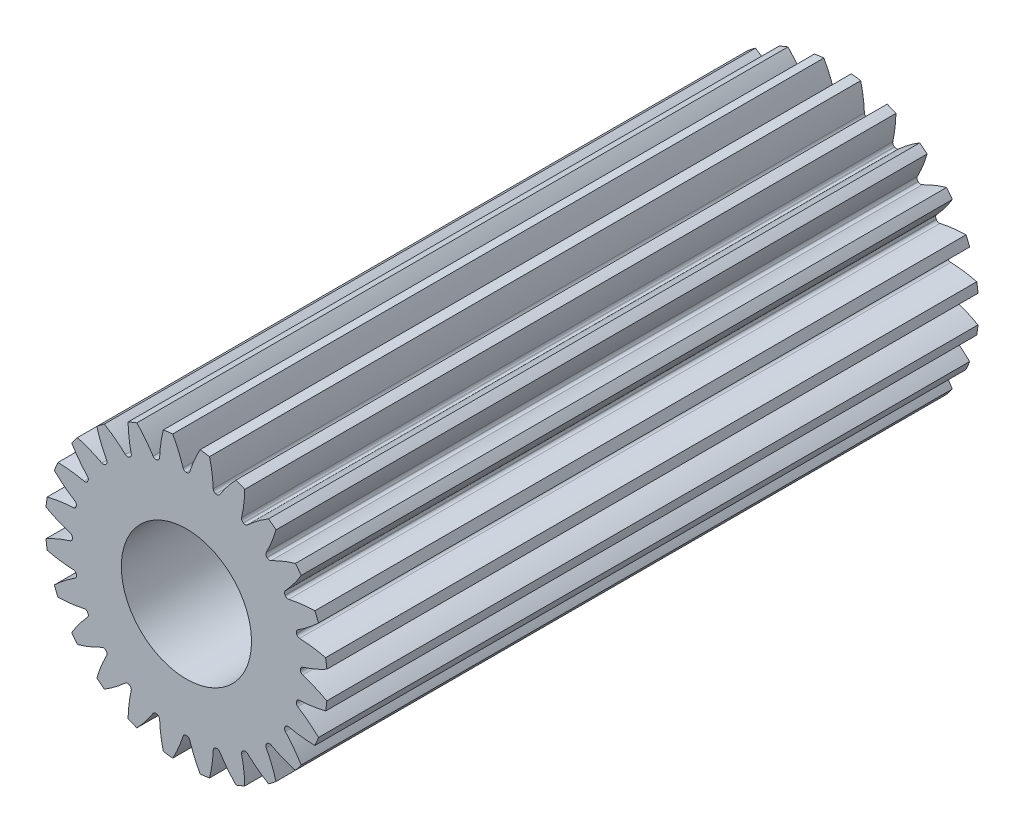
SolidWorks part; units mm, degrees
ref_plane "Front Plane" through (0, 0, 0) normal (0, 0, 1) x (1, 0, 0)
ref_plane "Top Plane" through (0, 0, 0) normal (0, 1, 0) x (1, 0, 0)
ref_plane "Right Plane" through (0, 0, 0) normal (1, 0, 0) x (0, 0, -1)
sketch "Sketch1" plane through (0, 0, 0) normal (0, 0, 1) x (1, 0, 0)
  line L0 (-304.8, 0) -> (304.8, 0) construction
  circle A0 centre (0, 0) radius 6.5 construction
  circle A1 centre (0, 0) radius 6 construction
  circle A2 centre (0, 0) radius 5.25 construction
  circle A3 centre (0, 0) radius 4 construction
  circle A4 centre (0, 0) radius 2 construction
  dimension "D2" = 0.5
  dimension "D3" = 1.25
  dimension "D1" = 1.25
sketch "Sketch2" plane through (0, 0, 0) normal (1, 0, 0) x (0, 0, -1)
  line L0 (0, 0) -> (-3, 0) construction
  line L1 (-3, 0) -> (-7, 0) construction
  dimension "Overall Width" = 7
  dimension "Face Width" = 3
sketch "Sketch4" plane through (0, 0, 0) normal (1, 0, 0) x (0, 0, -1)
  line L0 (-7, 2) -> (-7, 4) construction
  line L1 (-7, 4) -> (-3, 4) construction
  line L2 (-3, 4) -> (-3, 6.5)
  line L3 (-3, 6.5) -> (0, 6.5)
  line L4 (0, 6.5) -> (0, 2)
  line L5 (-3, 4) -> (-3, 0) construction
  line L6 (0, 6.5) -> (0, -6.5) construction
  line L7 (-3, 4) -> (0, 4) construction
  line L8 (-3, 4) -> (-3, 2)
  line L9 (-3, 2) -> (0, 2) construction
  line L10 (0, 2) -> (0, 0)
  line L11 (0, 0) -> (-3, 0)
  line L12 (-7, 2) -> (0, 2) construction
  line L13 (-3, 0) -> (-3, 2)
revolve "Revolve1" add sketch "Sketch4" angle 360 about L1
sketch "Sketch7" plane through (0, 0, 3) normal (0, 0, 1) x (1, 0, 0)
  line L0 (0, 0) -> (0, 6.5) construction
  line L1 (0.3924, 5.9872) -> (0.6056, 6.4717) construction
  line L3 (0.8484, 6.4444) -> (0.7832, 5.9487) construction
  line L4 (0.7832, 5.9487) -> (0.6853, 5.2051) construction
  line L5 (0, 0) -> (0.6853, 5.2051) construction
  line L6 (0.3924, 5.9872) -> (0, 0) construction
  line L7 (0.3924, 5.9872) -> (0.4251, 6.4861) construction
  line L8 (0.3924, 5.9872) -> (0, 0) construction
  circle A0 centre (0, 0) radius 6.5 construction
  arc A1 (-0.0123, 5.25) -> (0.0123, 5.25) centre (0, 0) cw
  circle A2 centre (0, 0) radius 5.25 construction
  arc A3 (-0.3924, 5.9872) -> (0.3924, 5.9872) centre (0, 0) cw construction
  circle A4 centre (0, 0) radius 6 construction
  arc A5 (1.065, 6.4122) -> (0.6309, 6.4693) centre (0, 0) ccw construction
  arc A6 (0.3924, 5.9872) -> (1.1705, 5.8847) centre (0, 0) cw construction
  arc A7 (-0.6309, 6.4693) -> (0.6309, 6.4693) centre (0, 0) cw
  arc A8 (0.1559, 5.3554) -> (0.6309, 6.4693) centre (5.8843, 3.5707) cw
  arc A9 (-0.1559, 5.3554) -> (-0.6309, 6.4693) centre (-5.8843, 3.5707) ccw
  arc A10 (-0.0123, 5.25) -> (-0.1559, 5.3554) centre (-0.0126, 5.4) cw
  arc A11 (0.0123, 5.25) -> (0.1559, 5.3554) centre (0.0126, 5.4) ccw
  point P26 (-0.1237, 5.2485)
  point P29 (0.1237, 5.2485)
  dimension "D4" = 0.15
  dimension "D5" = 6
  dimension "D3" = 20
  dimension "D1" = 1.5708
  dimension "D2" = 0.7854
extrude "Cut-Extrude2" cut sketch "Sketch7" against normal through all
pattern_circular "CirPattern1" count 24 over 360 about axis through (0, 0, 0) along (0, 0, 1) of "Cut-Extrude2"
sketch "Sketch8" plane through (0, 0, 3) normal (0, 0, 1) x (1, 0, 0)
  arc A144 (-1.5366, 5.1326) -> (-2.2838, 6.0856) centre (-6.6079, 1.926) ccw
  arc A145 (-2.2838, 6.0856) -> (-2.6883, 5.918) centre (0, 0) ccw
  arc A146 (-2.6883, 5.918) -> (-2.5427, 4.7158) centre (3.3106, 6.0344) ccw
  arc A147 (-2.6143, 4.5528) -> (-2.5427, 4.7158) centre (-2.689, 4.6829) ccw
  arc A148 (-2.6143, 4.5528) -> (-2.6356, 4.5405) centre (0, 0) ccw
  arc A149 (-2.8127, 4.56) -> (-2.6356, 4.5405) centre (-2.7109, 4.6702) ccw
  arc A150 (-2.8127, 4.56) -> (-3.781, 5.2871) centre (-6.8813, 0.1502) ccw
  arc A151 (-3.781, 5.2871) -> (-4.1284, 5.0206) centre (0, 0) ccw
  arc A152 (-4.1284, 5.0206) -> (-3.6766, 3.897) centre (1.636, 6.6857) ccw
  arc A153 (-3.7036, 3.721) -> (-3.6766, 3.897) centre (-3.8094, 3.8273) ccw
  arc A154 (-3.7036, 3.721) -> (-3.721, 3.7036) centre (0, 0) ccw
  arc A155 (-3.897, 3.6766) -> (-3.721, 3.7036) centre (-3.8273, 3.8094) ccw
  arc A156 (-3.897, 3.6766) -> (-5.0206, 4.1284) centre (-6.6857, -1.636) ccw
  arc A157 (-5.0206, 4.1284) -> (-5.2871, 3.781) centre (0, 0) ccw
  arc A158 (-5.2871, 3.781) -> (-4.56, 2.8127) centre (-0.1502, 6.8813) ccw
  arc A159 (-4.5405, 2.6356) -> (-4.56, 2.8127) centre (-4.6702, 2.7109) ccw
  arc A160 (-4.5405, 2.6356) -> (-4.5528, 2.6143) centre (0, 0) ccw
  arc A161 (-4.7158, 2.5427) -> (-4.5528, 2.6143) centre (-4.6829, 2.689) ccw
  arc A162 (-4.7158, 2.5427) -> (-5.918, 2.6883) centre (-6.0344, -3.3106) ccw
  arc A163 (-5.918, 2.6883) -> (-6.0856, 2.2838) centre (0, 0) ccw
  arc A164 (-6.0856, 2.2838) -> (-5.1326, 1.5366) centre (-1.926, 6.6079) ccw
  arc A165 (-5.0679, 1.3707) -> (-5.1326, 1.5366) centre (-5.2127, 1.4098) ccw
  arc A166 (-5.0679, 1.3707) -> (-5.0743, 1.3469) centre (0, 0) ccw
  arc A167 (-5.2132, 1.2355) -> (-5.0743, 1.3469) centre (-5.2193, 1.3854) ccw
  arc A168 (-5.2132, 1.2355) -> (-6.4122, 1.065) centre (-4.972, -4.7596) ccw
  arc A169 (-6.4122, 1.065) -> (-6.4693, 0.6309) centre (0, 0) ccw
  arc A170 (-6.4693, 0.6309) -> (-5.3554, 0.1559) centre (-3.5707, 5.8843) ccw
  arc A171 (-5.25, 0.0123) -> (-5.3554, 0.1559) centre (-5.4, 0.0126) ccw
  arc A172 (-5.25, 0.0123) -> (-5.25, -0.0123) centre (0, 0) ccw
  arc A173 (-5.3554, -0.1559) -> (-5.25, -0.0123) centre (-5.4, -0.0126) ccw
  arc A174 (-5.3554, -0.1559) -> (-6.4693, -0.6309) centre (-3.5707, -5.8843) ccw
  arc A175 (-6.4693, -0.6309) -> (-6.4122, -1.065) centre (0, 0) ccw
  arc A176 (-6.4122, -1.065) -> (-5.2132, -1.2355) centre (-4.972, 4.7596) ccw
  arc A177 (-5.0743, -1.3469) -> (-5.2132, -1.2355) centre (-5.2193, -1.3854) ccw
  arc A178 (-5.0743, -1.3469) -> (-5.0679, -1.3707) centre (0, 0) ccw
  arc A179 (-5.1326, -1.5366) -> (-5.0679, -1.3707) centre (-5.2127, -1.4098) ccw
  arc A180 (-5.1326, -1.5366) -> (-6.0856, -2.2838) centre (-1.926, -6.6079) ccw
  arc A181 (-6.0856, -2.2838) -> (-5.918, -2.6883) centre (0, 0) ccw
  arc A182 (-5.918, -2.6883) -> (-4.7158, -2.5427) centre (-6.0344, 3.3106) ccw
  arc A183 (-4.5528, -2.6143) -> (-4.7158, -2.5427) centre (-4.6829, -2.689) ccw
  arc A184 (-4.5528, -2.6143) -> (-4.5405, -2.6356) centre (0, 0) ccw
  arc A185 (-4.56, -2.8127) -> (-4.5405, -2.6356) centre (-4.6702, -2.7109) ccw
  arc A186 (-4.56, -2.8127) -> (-5.2871, -3.781) centre (-0.1502, -6.8813) ccw
  arc A187 (-5.2871, -3.781) -> (-5.0206, -4.1284) centre (0, 0) ccw
  arc A188 (-5.0206, -4.1284) -> (-3.897, -3.6766) centre (-6.6857, 1.636) ccw
  arc A189 (-3.721, -3.7036) -> (-3.897, -3.6766) centre (-3.8273, -3.8094) ccw
  arc A190 (-3.721, -3.7036) -> (-3.7036, -3.721) centre (0, 0) ccw
  arc A191 (-3.6766, -3.897) -> (-3.7036, -3.721) centre (-3.8094, -3.8273) ccw
  arc A192 (-3.6766, -3.897) -> (-4.1284, -5.0206) centre (1.636, -6.6857) ccw
  arc A193 (-4.1284, -5.0206) -> (-3.781, -5.2871) centre (0, 0) ccw
  arc A194 (-3.781, -5.2871) -> (-2.8127, -4.56) centre (-6.8813, -0.1502) ccw
  arc A195 (-2.6356, -4.5405) -> (-2.8127, -4.56) centre (-2.7109, -4.6702) ccw
  arc A196 (-2.6356, -4.5405) -> (-2.6143, -4.5528) centre (0, 0) ccw
  arc A197 (-2.5427, -4.7158) -> (-2.6143, -4.5528) centre (-2.689, -4.6829) ccw
  arc A198 (-2.5427, -4.7158) -> (-2.6883, -5.918) centre (3.3106, -6.0344) ccw
  arc A199 (-2.6883, -5.918) -> (-2.2838, -6.0856) centre (0, 0) ccw
  arc A200 (-2.2838, -6.0856) -> (-1.5366, -5.1326) centre (-6.6079, -1.926) ccw
  arc A201 (-1.3707, -5.0679) -> (-1.5366, -5.1326) centre (-1.4098, -5.2127) ccw
  arc A202 (-1.3707, -5.0679) -> (-1.3469, -5.0743) centre (0, 0) ccw
  arc A203 (-1.2355, -5.2132) -> (-1.3469, -5.0743) centre (-1.3854, -5.2193) ccw
  arc A204 (-1.2355, -5.2132) -> (-1.065, -6.4122) centre (4.7596, -4.972) ccw
  arc A205 (-1.065, -6.4122) -> (-0.6309, -6.4693) centre (0, 0) ccw
  arc A206 (-0.6309, -6.4693) -> (-0.1559, -5.3554) centre (-5.8843, -3.5707) ccw
  arc A207 (-0.0123, -5.25) -> (-0.1559, -5.3554) centre (-0.0126, -5.4) ccw
  arc A208 (-0.0123, -5.25) -> (0.0123, -5.25) centre (0, 0) ccw
  arc A209 (0.1559, -5.3554) -> (0.0123, -5.25) centre (0.0126, -5.4) ccw
  arc A210 (0.1559, -5.3554) -> (0.6309, -6.4693) centre (5.8843, -3.5707) ccw
  arc A211 (0.6309, -6.4693) -> (1.065, -6.4122) centre (0, 0) ccw
  arc A212 (1.065, -6.4122) -> (1.2355, -5.2132) centre (-4.7596, -4.972) ccw
  arc A213 (1.3469, -5.0743) -> (1.2355, -5.2132) centre (1.3854, -5.2193) ccw
  arc A214 (1.3469, -5.0743) -> (1.3707, -5.0679) centre (0, 0) ccw
  arc A215 (1.5366, -5.1326) -> (1.3707, -5.0679) centre (1.4098, -5.2127) ccw
  arc A216 (1.5366, -5.1326) -> (2.2838, -6.0856) centre (6.6079, -1.926) ccw
  arc A217 (2.2838, -6.0856) -> (2.6883, -5.918) centre (0, 0) ccw
  arc A218 (2.6883, -5.918) -> (2.5427, -4.7158) centre (-3.3106, -6.0344) ccw
  arc A219 (2.6143, -4.5528) -> (2.5427, -4.7158) centre (2.689, -4.6829) ccw
  arc A220 (2.6143, -4.5528) -> (2.6356, -4.5405) centre (0, 0) ccw
  arc A221 (2.8127, -4.56) -> (2.6356, -4.5405) centre (2.7109, -4.6702) ccw
  arc A222 (2.8127, -4.56) -> (3.781, -5.2871) centre (6.8813, -0.1502) ccw
  arc A223 (3.781, -5.2871) -> (4.1284, -5.0206) centre (0, 0) ccw
  arc A224 (4.1284, -5.0206) -> (3.6766, -3.897) centre (-1.636, -6.6857) ccw
  arc A225 (3.7036, -3.721) -> (3.6766, -3.897) centre (3.8094, -3.8273) ccw
  arc A226 (3.7036, -3.721) -> (3.721, -3.7036) centre (0, 0) ccw
  arc A227 (3.897, -3.6766) -> (3.721, -3.7036) centre (3.8273, -3.8094) ccw
  arc A228 (3.897, -3.6766) -> (5.0206, -4.1284) centre (6.6857, 1.636) ccw
  arc A229 (5.0206, -4.1284) -> (5.2871, -3.781) centre (0, 0) ccw
  arc A230 (5.2871, -3.781) -> (4.56, -2.8127) centre (0.1502, -6.8813) ccw
  arc A231 (4.5405, -2.6356) -> (4.56, -2.8127) centre (4.6702, -2.7109) ccw
  arc A232 (4.5405, -2.6356) -> (4.5528, -2.6143) centre (0, 0) ccw
  arc A233 (4.7158, -2.5427) -> (4.5528, -2.6143) centre (4.6829, -2.689) ccw
  arc A234 (4.7158, -2.5427) -> (5.918, -2.6883) centre (6.0344, 3.3106) ccw
  arc A235 (5.918, -2.6883) -> (6.0856, -2.2838) centre (0, 0) ccw
  arc A236 (6.0856, -2.2838) -> (5.1326, -1.5366) centre (1.926, -6.6079) ccw
  arc A237 (5.0679, -1.3707) -> (5.1326, -1.5366) centre (5.2127, -1.4098) ccw
  arc A238 (5.0679, -1.3707) -> (5.0743, -1.3469) centre (0, 0) ccw
  arc A239 (5.2132, -1.2355) -> (5.0743, -1.3469) centre (5.2193, -1.3854) ccw
  arc A240 (5.2132, -1.2355) -> (6.4122, -1.065) centre (4.972, 4.7596) ccw
  arc A241 (6.4122, -1.065) -> (6.4693, -0.6309) centre (0, 0) ccw
  arc A242 (6.4693, -0.6309) -> (5.3554, -0.1559) centre (3.5707, -5.8843) ccw
  arc A243 (5.25, -0.0123) -> (5.3554, -0.1559) centre (5.4, -0.0126) ccw
  arc A244 (5.25, -0.0123) -> (5.25, 0.0123) centre (0, 0) ccw
  arc A245 (5.3554, 0.1559) -> (5.25, 0.0123) centre (5.4, 0.0126) ccw
  arc A246 (5.3554, 0.1559) -> (6.4693, 0.6309) centre (3.5707, 5.8843) ccw
  arc A247 (6.4693, 0.6309) -> (6.4122, 1.065) centre (0, 0) ccw
  arc A248 (6.4122, 1.065) -> (5.2132, 1.2355) centre (4.972, -4.7596) ccw
  arc A249 (5.0743, 1.3469) -> (5.2132, 1.2355) centre (5.2193, 1.3854) ccw
  arc A250 (5.0743, 1.3469) -> (5.0679, 1.3707) centre (0, 0) ccw
  arc A251 (5.1326, 1.5366) -> (5.0679, 1.3707) centre (5.2127, 1.4098) ccw
  arc A252 (5.1326, 1.5366) -> (6.0856, 2.2838) centre (1.926, 6.6079) ccw
  arc A253 (6.0856, 2.2838) -> (5.918, 2.6883) centre (0, 0) ccw
  arc A254 (5.918, 2.6883) -> (4.7158, 2.5427) centre (6.0344, -3.3106) ccw
  arc A255 (4.5528, 2.6143) -> (4.7158, 2.5427) centre (4.6829, 2.689) ccw
  arc A256 (4.5528, 2.6143) -> (4.5405, 2.6356) centre (0, 0) ccw
  arc A257 (4.56, 2.8127) -> (4.5405, 2.6356) centre (4.6702, 2.7109) ccw
  arc A258 (4.56, 2.8127) -> (5.2871, 3.781) centre (0.1502, 6.8813) ccw
  arc A259 (5.2871, 3.781) -> (5.0206, 4.1284) centre (0, 0) ccw
  arc A260 (5.0206, 4.1284) -> (3.897, 3.6766) centre (6.6857, -1.636) ccw
  arc A261 (3.721, 3.7036) -> (3.897, 3.6766) centre (3.8273, 3.8094) ccw
  arc A262 (3.721, 3.7036) -> (3.7036, 3.721) centre (0, 0) ccw
  arc A263 (3.6766, 3.897) -> (3.7036, 3.721) centre (3.8094, 3.8273) ccw
  arc A264 (3.6766, 3.897) -> (4.1284, 5.0206) centre (-1.636, 6.6857) ccw
  arc A265 (4.1284, 5.0206) -> (3.781, 5.2871) centre (0, 0) ccw
  arc A266 (3.781, 5.2871) -> (2.8127, 4.56) centre (6.8813, 0.1502) ccw
  arc A267 (2.6356, 4.5405) -> (2.8127, 4.56) centre (2.7109, 4.6702) ccw
  arc A268 (2.6356, 4.5405) -> (2.6143, 4.5528) centre (0, 0) ccw
  arc A269 (2.5427, 4.7158) -> (2.6143, 4.5528) centre (2.689, 4.6829) ccw
  arc A270 (2.5427, 4.7158) -> (2.6883, 5.918) centre (-3.3106, 6.0344) ccw
  arc A271 (2.6883, 5.918) -> (2.2838, 6.0856) centre (0, 0) ccw
  arc A272 (2.2838, 6.0856) -> (1.5366, 5.1326) centre (6.6079, 1.926) ccw
  arc A273 (1.3707, 5.0679) -> (1.5366, 5.1326) centre (1.4098, 5.2127) ccw
  arc A274 (1.3707, 5.0679) -> (1.3469, 5.0743) centre (0, 0) ccw
  arc A275 (1.2355, 5.2132) -> (1.3469, 5.0743) centre (1.3854, 5.2193) ccw
  arc A276 (1.2355, 5.2132) -> (1.065, 6.4122) centre (-4.7596, 4.972) ccw
  arc A277 (1.065, 6.4122) -> (0.6309, 6.4693) centre (0, 0) ccw
  arc A278 (0.6309, 6.4693) -> (0.1559, 5.3554) centre (5.8843, 3.5707) ccw
  arc A279 (0.0123, 5.25) -> (0.1559, 5.3554) centre (0.0126, 5.4) ccw
  arc A280 (0.0123, 5.25) -> (-0.0123, 5.25) centre (0, 0) ccw
  arc A281 (-0.1559, 5.3554) -> (-0.0123, 5.25) centre (-0.0126, 5.4) ccw
  arc A282 (-0.1559, 5.3554) -> (-0.6309, 6.4693) centre (-5.8843, 3.5707) ccw
  arc A283 (-0.6309, 6.4693) -> (-1.065, 6.4122) centre (0, 0) ccw
  arc A284 (-1.065, 6.4122) -> (-1.2355, 5.2132) centre (4.7596, 4.972) ccw
  arc A285 (-1.3469, 5.0743) -> (-1.2355, 5.2132) centre (-1.3854, 5.2193) ccw
  arc A286 (-1.3469, 5.0743) -> (-1.3707, 5.0679) centre (0, 0) ccw
  arc A287 (-1.5366, 5.1326) -> (-1.3707, 5.0679) centre (-1.4098, 5.2127) ccw
  arc A288 (-1.5366, 5.1326) -> (-2.2838, 6.0856) centre (-6.6079, 1.926) ccw
  arc A289 (-2.2838, 6.0856) -> (-2.6883, 5.918) centre (0, 0) ccw
  arc A290 (-2.6883, 5.918) -> (-2.5427, 4.7158) centre (3.3106, 6.0344) ccw
  arc A291 (-2.6143, 4.5528) -> (-2.5427, 4.7158) centre (-2.689, 4.6829) ccw
  arc A292 (-2.6143, 4.5528) -> (-2.6356, 4.5405) centre (0, 0) ccw
  arc A293 (-2.8127, 4.56) -> (-2.6356, 4.5405) centre (-2.7109, 4.6702) ccw
  arc A294 (-2.8127, 4.56) -> (-3.781, 5.2871) centre (-6.8813, 0.1502) ccw
  arc A295 (-3.781, 5.2871) -> (-4.1284, 5.0206) centre (0, 0) ccw
  arc A296 (-4.1284, 5.0206) -> (-3.6766, 3.897) centre (1.636, 6.6857) ccw
  arc A297 (-3.7036, 3.721) -> (-3.6766, 3.897) centre (-3.8094, 3.8273) ccw
  arc A298 (-3.7036, 3.721) -> (-3.721, 3.7036) centre (0, 0) ccw
  arc A299 (-3.897, 3.6766) -> (-3.721, 3.7036) centre (-3.8273, 3.8094) ccw
  arc A300 (-3.897, 3.6766) -> (-5.0206, 4.1284) centre (-6.6857, -1.636) ccw
  arc A301 (-5.0206, 4.1284) -> (-5.2871, 3.781) centre (0, 0) ccw
  arc A302 (-5.2871, 3.781) -> (-4.56, 2.8127) centre (-0.1502, 6.8813) ccw
  arc A303 (-4.5405, 2.6356) -> (-4.56, 2.8127) centre (-4.6702, 2.7109) ccw
  arc A304 (-4.5405, 2.6356) -> (-4.5528, 2.6143) centre (0, 0) ccw
  arc A305 (-4.7158, 2.5427) -> (-4.5528, 2.6143) centre (-4.6829, 2.689) ccw
  arc A306 (-4.7158, 2.5427) -> (-5.918, 2.6883) centre (-6.0344, -3.3106) ccw
  arc A307 (-5.918, 2.6883) -> (-6.0856, 2.2838) centre (0, 0) ccw
  arc A308 (-6.0856, 2.2838) -> (-5.1326, 1.5366) centre (-1.926, 6.6079) ccw
  arc A309 (-5.0679, 1.3707) -> (-5.1326, 1.5366) centre (-5.2127, 1.4098) ccw
  arc A310 (-5.0679, 1.3707) -> (-5.0743, 1.3469) centre (0, 0) ccw
  arc A311 (-5.2132, 1.2355) -> (-5.0743, 1.3469) centre (-5.2193, 1.3854) ccw
  arc A312 (-5.2132, 1.2355) -> (-6.4122, 1.065) centre (-4.972, -4.7596) ccw
  arc A313 (-6.4122, 1.065) -> (-6.4693, 0.6309) centre (0, 0) ccw
  arc A314 (-6.4693, 0.6309) -> (-5.3554, 0.1559) centre (-3.5707, 5.8843) ccw
  arc A315 (-5.25, 0.0123) -> (-5.3554, 0.1559) centre (-5.4, 0.0126) ccw
  arc A316 (-5.25, 0.0123) -> (-5.25, -0.0123) centre (0, 0) ccw
  arc A317 (-5.3554, -0.1559) -> (-5.25, -0.0123) centre (-5.4, -0.0126) ccw
  arc A318 (-5.3554, -0.1559) -> (-6.4693, -0.6309) centre (-3.5707, -5.8843) ccw
  arc A319 (-6.4693, -0.6309) -> (-6.4122, -1.065) centre (0, 0) ccw
  arc A320 (-6.4122, -1.065) -> (-5.2132, -1.2355) centre (-4.972, 4.7596) ccw
  arc A321 (-5.0743, -1.3469) -> (-5.2132, -1.2355) centre (-5.2193, -1.3854) ccw
  arc A322 (-5.0743, -1.3469) -> (-5.0679, -1.3707) centre (0, 0) ccw
  arc A323 (-5.1326, -1.5366) -> (-5.0679, -1.3707) centre (-5.2127, -1.4098) ccw
  arc A324 (-5.1326, -1.5366) -> (-6.0856, -2.2838) centre (-1.926, -6.6079) ccw
  arc A325 (-6.0856, -2.2838) -> (-5.918, -2.6883) centre (0, 0) ccw
  arc A326 (-5.918, -2.6883) -> (-4.7158, -2.5427) centre (-6.0344, 3.3106) ccw
  arc A327 (-4.5528, -2.6143) -> (-4.7158, -2.5427) centre (-4.6829, -2.689) ccw
  arc A328 (-4.5528, -2.6143) -> (-4.5405, -2.6356) centre (0, 0) ccw
  arc A329 (-4.56, -2.8127) -> (-4.5405, -2.6356) centre (-4.6702, -2.7109) ccw
  arc A330 (-4.56, -2.8127) -> (-5.2871, -3.781) centre (-0.1502, -6.8813) ccw
  arc A331 (-5.2871, -3.781) -> (-5.0206, -4.1284) centre (0, 0) ccw
  arc A332 (-5.0206, -4.1284) -> (-3.897, -3.6766) centre (-6.6857, 1.636) ccw
  arc A333 (-3.721, -3.7036) -> (-3.897, -3.6766) centre (-3.8273, -3.8094) ccw
  arc A334 (-3.721, -3.7036) -> (-3.7036, -3.721) centre (0, 0) ccw
  arc A335 (-3.6766, -3.897) -> (-3.7036, -3.721) centre (-3.8094, -3.8273) ccw
  arc A336 (-3.6766, -3.897) -> (-4.1284, -5.0206) centre (1.636, -6.6857) ccw
  arc A337 (-4.1284, -5.0206) -> (-3.781, -5.2871) centre (0, 0) ccw
  arc A338 (-3.781, -5.2871) -> (-2.8127, -4.56) centre (-6.8813, -0.1502) ccw
  arc A339 (-2.6356, -4.5405) -> (-2.8127, -4.56) centre (-2.7109, -4.6702) ccw
  arc A340 (-2.6356, -4.5405) -> (-2.6143, -4.5528) centre (0, 0) ccw
  arc A341 (-2.5427, -4.7158) -> (-2.6143, -4.5528) centre (-2.689, -4.6829) ccw
  arc A342 (-2.5427, -4.7158) -> (-2.6883, -5.918) centre (3.3106, -6.0344) ccw
  arc A343 (-2.6883, -5.918) -> (-2.2838, -6.0856) centre (0, 0) ccw
  arc A344 (-2.2838, -6.0856) -> (-1.5366, -5.1326) centre (-6.6079, -1.926) ccw
  arc A345 (-1.3707, -5.0679) -> (-1.5366, -5.1326) centre (-1.4098, -5.2127) ccw
  arc A346 (-1.3707, -5.0679) -> (-1.3469, -5.0743) centre (0, 0) ccw
  arc A347 (-1.2355, -5.2132) -> (-1.3469, -5.0743) centre (-1.3854, -5.2193) ccw
  arc A348 (-1.2355, -5.2132) -> (-1.065, -6.4122) centre (4.7596, -4.972) ccw
  arc A349 (-1.065, -6.4122) -> (-0.6309, -6.4693) centre (0, 0) ccw
  arc A350 (-0.6309, -6.4693) -> (-0.1559, -5.3554) centre (-5.8843, -3.5707) ccw
  arc A351 (-0.0123, -5.25) -> (-0.1559, -5.3554) centre (-0.0126, -5.4) ccw
  arc A352 (-0.0123, -5.25) -> (0.0123, -5.25) centre (0, 0) ccw
  arc A353 (0.1559, -5.3554) -> (0.0123, -5.25) centre (0.0126, -5.4) ccw
  arc A354 (0.1559, -5.3554) -> (0.6309, -6.4693) centre (5.8843, -3.5707) ccw
  arc A355 (0.6309, -6.4693) -> (1.065, -6.4122) centre (0, 0) ccw
  arc A356 (1.065, -6.4122) -> (1.2355, -5.2132) centre (-4.7596, -4.972) ccw
  arc A357 (1.3469, -5.0743) -> (1.2355, -5.2132) centre (1.3854, -5.2193) ccw
  arc A358 (1.3469, -5.0743) -> (1.3707, -5.0679) centre (0, 0) ccw
  arc A359 (1.5366, -5.1326) -> (1.3707, -5.0679) centre (1.4098, -5.2127) ccw
  arc A360 (1.5366, -5.1326) -> (2.2838, -6.0856) centre (6.6079, -1.926) ccw
  arc A361 (2.2838, -6.0856) -> (2.6883, -5.918) centre (0, 0) ccw
  arc A362 (2.6883, -5.918) -> (2.5427, -4.7158) centre (-3.3106, -6.0344) ccw
  arc A363 (2.6143, -4.5528) -> (2.5427, -4.7158) centre (2.689, -4.6829) ccw
  arc A364 (2.6143, -4.5528) -> (2.6356, -4.5405) centre (0, 0) ccw
  arc A365 (2.8127, -4.56) -> (2.6356, -4.5405) centre (2.7109, -4.6702) ccw
  arc A366 (2.8127, -4.56) -> (3.781, -5.2871) centre (6.8813, -0.1502) ccw
  arc A367 (3.781, -5.2871) -> (4.1284, -5.0206) centre (0, 0) ccw
  arc A368 (4.1284, -5.0206) -> (3.6766, -3.897) centre (-1.636, -6.6857) ccw
  arc A369 (3.7036, -3.721) -> (3.6766, -3.897) centre (3.8094, -3.8273) ccw
  arc A370 (3.7036, -3.721) -> (3.721, -3.7036) centre (0, 0) ccw
  arc A371 (3.897, -3.6766) -> (3.721, -3.7036) centre (3.8273, -3.8094) ccw
  arc A372 (3.897, -3.6766) -> (5.0206, -4.1284) centre (6.6857, 1.636) ccw
  arc A373 (5.0206, -4.1284) -> (5.2871, -3.781) centre (0, 0) ccw
  arc A374 (5.2871, -3.781) -> (4.56, -2.8127) centre (0.1502, -6.8813) ccw
  arc A375 (4.5405, -2.6356) -> (4.56, -2.8127) centre (4.6702, -2.7109) ccw
  arc A376 (4.5405, -2.6356) -> (4.5528, -2.6143) centre (0, 0) ccw
  arc A377 (4.7158, -2.5427) -> (4.5528, -2.6143) centre (4.6829, -2.689) ccw
  arc A378 (4.7158, -2.5427) -> (5.918, -2.6883) centre (6.0344, 3.3106) ccw
  arc A379 (5.918, -2.6883) -> (6.0856, -2.2838) centre (0, 0) ccw
  arc A380 (6.0856, -2.2838) -> (5.1326, -1.5366) centre (1.926, -6.6079) ccw
  arc A381 (5.0679, -1.3707) -> (5.1326, -1.5366) centre (5.2127, -1.4098) ccw
  arc A382 (5.0679, -1.3707) -> (5.0743, -1.3469) centre (0, 0) ccw
  arc A383 (5.2132, -1.2355) -> (5.0743, -1.3469) centre (5.2193, -1.3854) ccw
  arc A384 (5.2132, -1.2355) -> (6.4122, -1.065) centre (4.972, 4.7596) ccw
  arc A385 (6.4122, -1.065) -> (6.4693, -0.6309) centre (0, 0) ccw
  arc A386 (6.4693, -0.6309) -> (5.3554, -0.1559) centre (3.5707, -5.8843) ccw
  arc A387 (5.25, -0.0123) -> (5.3554, -0.1559) centre (5.4, -0.0126) ccw
  arc A388 (5.25, -0.0123) -> (5.25, 0.0123) centre (0, 0) ccw
  arc A389 (5.3554, 0.1559) -> (5.25, 0.0123) centre (5.4, 0.0126) ccw
  arc A390 (5.3554, 0.1559) -> (6.4693, 0.6309) centre (3.5707, 5.8843) ccw
  arc A391 (6.4693, 0.6309) -> (6.4122, 1.065) centre (0, 0) ccw
  arc A392 (6.4122, 1.065) -> (5.2132, 1.2355) centre (4.972, -4.7596) ccw
  arc A393 (5.0743, 1.3469) -> (5.2132, 1.2355) centre (5.2193, 1.3854) ccw
  arc A394 (5.0743, 1.3469) -> (5.0679, 1.3707) centre (0, 0) ccw
  arc A395 (5.1326, 1.5366) -> (5.0679, 1.3707) centre (5.2127, 1.4098) ccw
  arc A396 (5.1326, 1.5366) -> (6.0856, 2.2838) centre (1.926, 6.6079) ccw
  arc A397 (6.0856, 2.2838) -> (5.918, 2.6883) centre (0, 0) ccw
  arc A398 (5.918, 2.6883) -> (4.7158, 2.5427) centre (6.0344, -3.3106) ccw
  arc A399 (4.5528, 2.6143) -> (4.7158, 2.5427) centre (4.6829, 2.689) ccw
  arc A400 (4.5528, 2.6143) -> (4.5405, 2.6356) centre (0, 0) ccw
  arc A401 (4.56, 2.8127) -> (4.5405, 2.6356) centre (4.6702, 2.7109) ccw
  arc A402 (4.56, 2.8127) -> (5.2871, 3.781) centre (0.1502, 6.8813) ccw
  arc A403 (5.2871, 3.781) -> (5.0206, 4.1284) centre (0, 0) ccw
  arc A404 (5.0206, 4.1284) -> (3.897, 3.6766) centre (6.6857, -1.636) ccw
  arc A405 (3.721, 3.7036) -> (3.897, 3.6766) centre (3.8273, 3.8094) ccw
  arc A406 (3.721, 3.7036) -> (3.7036, 3.721) centre (0, 0) ccw
  arc A407 (3.6766, 3.897) -> (3.7036, 3.721) centre (3.8094, 3.8273) ccw
  arc A408 (3.6766, 3.897) -> (4.1284, 5.0206) centre (-1.636, 6.6857) ccw
  arc A409 (4.1284, 5.0206) -> (3.781, 5.2871) centre (0, 0) ccw
  arc A410 (3.781, 5.2871) -> (2.8127, 4.56) centre (6.8813, 0.1502) ccw
  arc A411 (2.6356, 4.5405) -> (2.8127, 4.56) centre (2.7109, 4.6702) ccw
  arc A412 (2.6356, 4.5405) -> (2.6143, 4.5528) centre (0, 0) ccw
  arc A413 (2.5427, 4.7158) -> (2.6143, 4.5528) centre (2.689, 4.6829) ccw
  arc A414 (2.5427, 4.7158) -> (2.6883, 5.918) centre (-3.3106, 6.0344) ccw
  arc A415 (2.6883, 5.918) -> (2.2838, 6.0856) centre (0, 0) ccw
  arc A416 (2.2838, 6.0856) -> (1.5366, 5.1326) centre (6.6079, 1.926) ccw
  arc A417 (1.3707, 5.0679) -> (1.5366, 5.1326) centre (1.4098, 5.2127) ccw
  arc A418 (1.3707, 5.0679) -> (1.3469, 5.0743) centre (0, 0) ccw
  arc A419 (1.2355, 5.2132) -> (1.3469, 5.0743) centre (1.3854, 5.2193) ccw
  arc A420 (1.2355, 5.2132) -> (1.065, 6.4122) centre (-4.7596, 4.972) ccw
  arc A421 (1.065, 6.4122) -> (0.6309, 6.4693) centre (0, 0) ccw
  arc A422 (0.6309, 6.4693) -> (0.1559, 5.3554) centre (5.8843, 3.5707) ccw
  arc A423 (0.0123, 5.25) -> (0.1559, 5.3554) centre (0.0126, 5.4) ccw
  arc A424 (0.0123, 5.25) -> (-0.0123, 5.25) centre (0, 0) ccw
  arc A425 (-0.1559, 5.3554) -> (-0.0123, 5.25) centre (-0.0126, 5.4) ccw
  arc A426 (-0.1559, 5.3554) -> (-0.6309, 6.4693) centre (-5.8843, 3.5707) ccw
  arc A427 (-0.6309, 6.4693) -> (-1.065, 6.4122) centre (0, 0) ccw
  arc A428 (-1.065, 6.4122) -> (-1.2355, 5.2132) centre (4.7596, 4.972) ccw
  arc A429 (-1.3469, 5.0743) -> (-1.2355, 5.2132) centre (-1.3854, 5.2193) ccw
  arc A430 (-1.3469, 5.0743) -> (-1.3707, 5.0679) centre (0, 0) ccw
  arc A431 (-1.5366, 5.1326) -> (-1.3707, 5.0679) centre (-1.4098, 5.2127) ccw
  dimension "D1" = 0
extrude "Boss-Extrude1" add sketch "Sketch8" along normal blind 27
sketch "Sketch9" plane through (0, 0, 0) normal (0, 0, -1) x (-1, 0, 0)
  line L0 (-1.4283, 1.4) -> (1.4283, 1.4)
  circle A0 centre (0, 0) radius 2 construction
  arc A1 (-1.4283, 1.4) -> (1.4283, 1.4) centre (0, 0) ccw
  dimension "D1" = 3.4
  dimension "D2" = 4
extrude "Cut-Extrude3" cut sketch "Sketch9" against normal blind 10
sketch "Sketch10" plane through (0, 0, 30) normal (0, 0, 1) x (1, 0, 0)
  circle A0 centre (0, 0) radius 3
  dimension "D1" = 6
extrude "Cut-Extrude4" cut sketch "Sketch10" against normal blind 10
equation "\"D1@Sketch1\"=2.5*(\"Pitch Dia.@Sketch1\"/\"Number of Teeth@Sketch1\")"
equation "\"D1@CirPattern1\"=\"Number of Teeth@Sketch1\""
equation "\"D1@Sketch7\"=3.14159*(\"Pitch Dia.@Sketch1\"/\"Number of Teeth@Sketch1\")"
equation "\"D2@Sketch7\"=\"D1@Sketch7\"/2"
equation "\"D4@Sketch7\"=\"D1@Sketch7\"*.0955"
equation "\"D5@Sketch7\"=\"Pitch Dia.@Sketch1\"/2"
